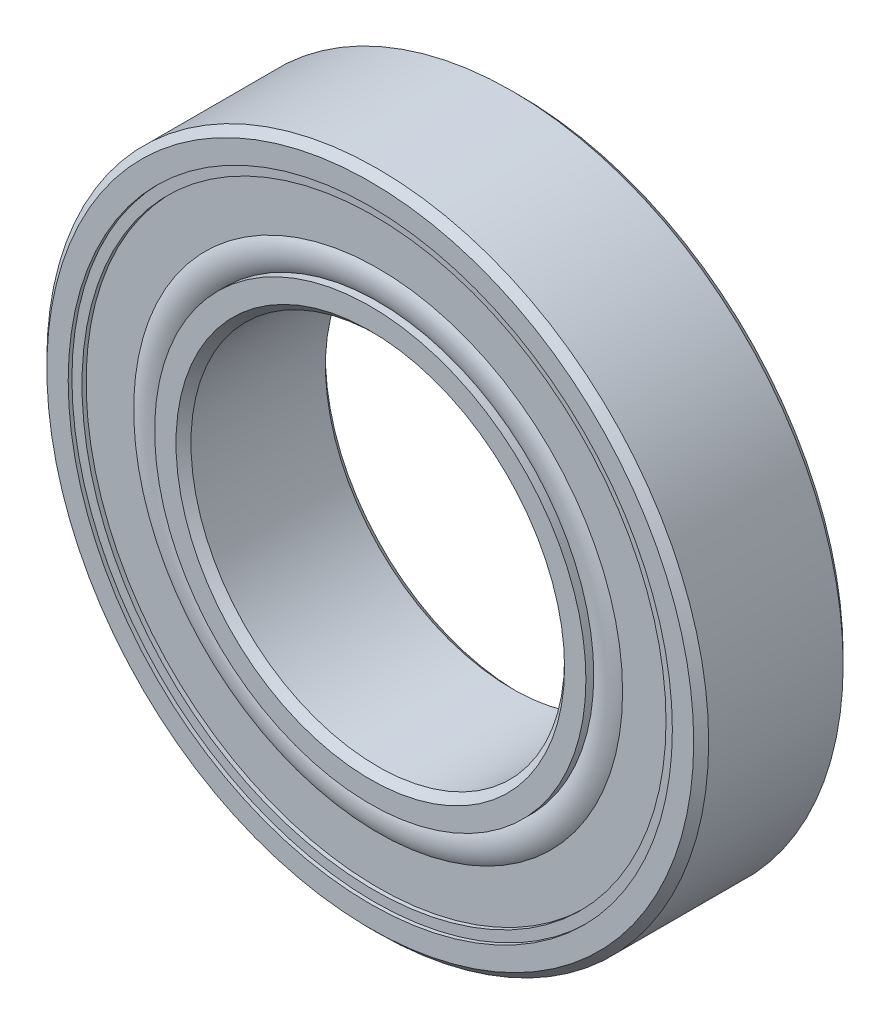
SolidWorks part; units mm, degrees
ref_plane "Front Plane" through (0, 0, 0) normal (0, 0, 1) x (1, 0, 0)
ref_plane "Top Plane" through (0, 0, 0) normal (0, 1, 0) x (1, 0, 0)
ref_plane "Right Plane" through (0, 0, 0) normal (1, 0, 0) x (0, 0, -1)
sketch "Sketch1" plane through (0, 0, 0) normal (0, 0, 1) x (1, 0, 0)
  circle A0 centre (0, 0) radius 31 construction
  circle A1 centre (0, 0) radius 17.5 construction
  dimension "OD" = 62
  dimension "ID" = 35
sketch "Sketch2" plane through (0, 0, 0) normal (1, 0, 0) x (0, 0, -1)
  line L0 (-7, 0) -> (7, 0) construction
  line L1 (0, 31) -> (0, -31) construction
  line L2 (6.3, 31) -> (-6.3, 31) construction
  line L3 (-6.3, 31) -> (-7, 30.3) construction
  line L4 (-7, 30.3) -> (-7, 28.3) construction
  line L5 (-7, 28.3) -> (-3.1111, 28.3) construction
  line L6 (7, 28.3) -> (3.1111, 28.3) construction
  line L7 (7, 30.3) -> (7, 28.3) construction
  line L8 (6.3, 31) -> (7, 30.3) construction
  line L9 (0, 31) -> (0, 24.25) construction
  line L10 (0, 24.25) -> (0, 17.5) construction
  line L11 (7, 24.25) -> (-7, 24.25) construction
  line L12 (-7, 18.2) -> (-7, 20.2) construction
  line L13 (-6.3, 17.5) -> (-7, 18.2) construction
  line L14 (6.3, 17.5) -> (-6.3, 17.5) construction
  line L15 (6.3, 17.5) -> (7, 18.2) construction
  line L16 (7, 18.2) -> (7, 20.2) construction
  line L17 (7, 20.2) -> (3.1111, 20.2) construction
  line L18 (-7, 20.2) -> (-3.1111, 20.2) construction
  line L19 (-7, 17.5) -> (-7, -17.5) construction
  line L20 (7, 31) -> (7, -31) construction
  arc A0 (-3.1111, 28.3) -> (3.1111, 28.3) centre (0, 24.25) cw construction
  arc A1 (-3.1111, 20.2) -> (3.1111, 20.2) centre (0, 24.25) ccw construction
  point P14 (0, 17.5)
  point P18 (0, 24.25)
  dimension "Approx. Ball Dia." = 10.214
  dimension "D1" = 45
  dimension "D2" = 0.7
  dimension "D3" = 6.2222
  dimension "D4" = 4.05
  dimension "Width" = 14
  dimension "For Shaft Diameter" = 35
  dimension "For Housing ID" = 62
sketch "Sketch3" plane through (0, 0, 0) normal (1, 0, 0) x (0, 0, -1)
  line L0 (-7, 30.3) -> (-7, 28.3) construction
  line L1 (-6.3, 31) -> (-7, 30.3) construction
  line L2 (6.3, 31) -> (-6.3, 31) construction
  line L3 (6.3, 31) -> (7, 30.3) construction
  line L4 (7, 30.3) -> (7, 28.3) construction
  line L5 (7, 28.3) -> (3.1111, 28.3) construction
  line L6 (-7, 28.3) -> (-3.1111, 28.3) construction
  line L7 (-7, 30.3) -> (-7, 28.3)
  line L8 (-6.3, 31) -> (-7, 30.3)
  line L9 (6.3, 31) -> (-6.3, 31)
  line L10 (6.3, 31) -> (7, 30.3)
  line L11 (7, 30.3) -> (7, 28.3)
  line L12 (7, 28.3) -> (3.1111, 28.3)
  line L13 (-7, 28.3) -> (-3.1111, 28.3)
  line L14 (-7, 18.2) -> (-7, 20.2) construction
  line L15 (-6.3, 17.5) -> (-7, 18.2) construction
  line L16 (6.3, 17.5) -> (-6.3, 17.5) construction
  line L17 (6.3, 17.5) -> (7, 18.2) construction
  line L18 (7, 18.2) -> (7, 20.2) construction
  line L19 (7, 20.2) -> (3.1111, 20.2) construction
  line L20 (-7, 20.2) -> (-3.1111, 20.2) construction
  line L21 (-7, 18.2) -> (-7, 20.2)
  line L22 (-6.3, 17.5) -> (-7, 18.2)
  line L23 (6.3, 17.5) -> (-6.3, 17.5)
  line L24 (6.3, 17.5) -> (7, 18.2)
  line L25 (7, 18.2) -> (7, 20.2)
  line L26 (7, 20.2) -> (3.1111, 20.2)
  line L27 (-7, 20.2) -> (-3.1111, 20.2)
  arc A0 (3.1111, 28.3) -> (-3.1111, 28.3) centre (0, 24.25) ccw construction
  arc A1 (3.1111, 28.3) -> (-3.1111, 28.3) centre (0, 24.25) ccw
  arc A2 (-3.1111, 20.2) -> (3.1111, 20.2) centre (0, 24.25) ccw construction
  arc A3 (-3.1111, 20.2) -> (3.1111, 20.2) centre (0, 24.25) ccw
revolve "Revolve1" add sketch "Sketch3" angle 360 about L0
sketch "Sketch4" plane through (0, 0, 0) normal (1, 0, 0) x (0, 0, -1)
  line L0 (-5.107, 24.25) -> (5.107, 24.25)
  arc A2 (-5.107, 24.25) -> (5.107, 24.25) centre (0, 24.25) cw
  arc A3 (3.1111, 28.3) -> (-3.1111, 28.3) centre (0, 24.25) ccw construction
revolve "Revolve2" add sketch "Sketch4" angle 360 about L0
pattern_circular "CirPattern1" count 10 over 360 about axis through (0, 0, 0) along (0, 0, 1) of bodies 104
sketch "Sketch5" plane through (0, 0, 0) normal (1, 0, 0) x (0, 0, -1)
  line L0 (-7, 28.3) -> (-3.1111, 28.3) construction
  line L1 (-6.65, 28.3) -> (-5.107, 28.3)
  line L2 (-6.65, 28.3) -> (-6.65, 27.355)
  line L3 (-6.65, 20.2) -> (-5.107, 20.2) construction
  line L4 (-5.107, 28.3) -> (-5.107, 20.2)
  line L5 (0, 31) -> (0, 0) construction
  line L7 (-6.65, 27.355) -> (-6.2643, 27.355)
  line L8 (-6.2643, 27.355) -> (-6.2643, 22.9)
  line L9 (-6.2643, 22.9) -> (-6.65, 22.9) construction
  line L10 (-6.65, 22.9) -> (-6.65, 20.2) construction
  line L11 (6.3, 31) -> (-6.3, 31) construction
  line L12 (-6.3, 31) -> (-7, 30.3) construction
  line L13 (-7, 20.2) -> (-3.1111, 20.2) construction
  line L15 (-6.2643, 20.2) -> (-5.107, 20.2)
  line L16 (6.65, 22.9) -> (6.65, 20.2) construction
  line L17 (6.2643, 22.9) -> (6.65, 22.9) construction
  line L18 (6.65, 20.2) -> (5.107, 20.2) construction
  line L19 (6.2643, 20.2) -> (5.107, 20.2)
  line L20 (6.2643, 27.355) -> (6.2643, 22.9)
  line L21 (6.65, 27.355) -> (6.2643, 27.355)
  line L22 (5.107, 28.3) -> (5.107, 20.2)
  line L23 (6.65, 28.3) -> (6.65, 27.355)
  line L24 (6.65, 28.3) -> (5.107, 28.3)
  arc A0 (-6.2643, 20.2) -> (-6.2643, 22.9) centre (-4.0948, 21.55) cw
  arc A1 (6.2643, 20.2) -> (6.2643, 22.9) centre (4.0948, 21.55) ccw
  point P10 (-6.2643, 20.2)
  point P18 (-6.65, 30.65)
  dimension "D1" = 0.945
  dimension "D2" = 2.7
  dimension "D3" = 1.543
  dimension "D4" = 0.3857
revolve "Revolve3" add sketch "Sketch5" angle 360 about L0
equation "\"D2@Sketch2\"= \"Width@Sketch2\" * .05"
equation "\"D3@Sketch2\"=\"Width@Sketch2\" / 2.25"
equation "\"D4@Sketch2\"=( \"OD@Sketch1\" - \"For Shaft Diameter@Sketch2\" ) *0.15"
equation "\"Approx. No. of Balls\"= ( pi * \"OD@Sketch1\" ) * .5 / \"Approx. Ball Dia.@Sketch2\""
equation "\"Balls@CirPattern1\"=\"Approx. No. of Balls\""
equation "\"D1@Sketch5\"=( \"OD@Sketch1\" - \"For Shaft Diameter@Sketch2\" ) *0.035"
equation "\"D2@Sketch5\"=( \"OD@Sketch1\" - \"For Shaft Diameter@Sketch2\" ) *0.1"
equation "\"D4@Sketch5\"=\"D3@Sketch5\"*.25"
